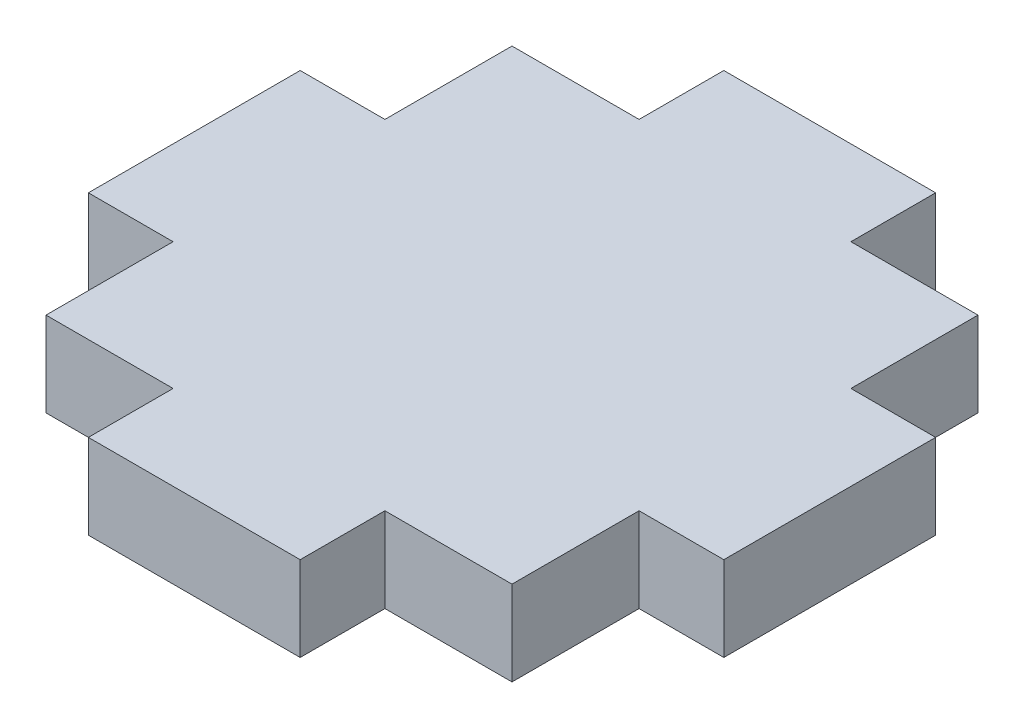
SolidWorks part; units mm, degrees
ref_plane "Front Plane" through (0, 0, 0) normal (0, 0, 1) x (1, 0, 0)
ref_plane "Top Plane" through (0, 0, 0) normal (0, 1, 0) x (1, 0, 0)
ref_plane "Right Plane" through (0, 0, 0) normal (1, 0, 0) x (0, 0, -1)
sketch "Sketch1" plane through (0, 0, 0) normal (0, 1, 0) x (1, 0, 0)
  line L1 (0, 0) -> (30, 0)
  line L2 (0, 0) -> (0, 30)
  line L3 (0, 30) -> (30, 30)
  line L4 (30, 0) -> (30, 30)
  line L9 (0, 30) -> (4, 30)
  line L10 (0, 30) -> (0, 0)
  line L11 (0, 0) -> (4, 0)
  line L12 (4, 30) -> (4, 0)
  line L13 (0, 0) -> (30, 0)
  line L14 (0, 0) -> (0, 4)
  line L15 (0, 4) -> (30, 4)
  line L16 (30, 0) -> (30, 4)
  line L17 (30, 0) -> (26, 0)
  line L18 (30, 0) -> (30, 30)
  line L19 (30, 30) -> (26, 30)
  line L20 (26, 0) -> (26, 30)
  line L21 (30, 30) -> (0, 30)
  line L22 (30, 30) -> (30, 26)
  line L23 (30, 26) -> (0, 26)
  line L24 (0, 30) -> (0, 26)
  line L25 (0, 20) -> (4, 20)
  line L26 (0, 20) -> (0, 10)
  line L27 (0, 10) -> (4, 10)
  line L28 (4, 20) -> (4, 10)
  line L29 (10, 26) -> (20, 26)
  line L30 (10, 26) -> (10, 30)
  line L31 (10, 30) -> (20, 30)
  line L32 (20, 26) -> (20, 30)
  line L33 (26, 20) -> (30, 20)
  line L34 (26, 20) -> (26, 10)
  line L35 (26, 10) -> (30, 10)
  line L36 (30, 20) -> (30, 10)
  line L37 (20, 4) -> (10, 4)
  line L38 (20, 4) -> (20, 0)
  line L39 (20, 0) -> (10, 0)
  line L40 (10, 4) -> (10, 0)
  point P29 (10, 2)
  dimension "D1" = 30
  dimension "D2" = 30
  dimension "D3" = 4
  dimension "D4" = 4
  dimension "D5" = 4
  dimension "D6" = 4
  dimension "D7" = 10
  dimension "D8" = 10
  dimension "D9" = 10
  dimension "D10" = 10
  dimension "D11" = 10
  dimension "D12" = 10
  dimension "D13" = 10
  dimension "D14" = 10
extrude "Boss-Extrude1" add sketch "Sketch1" along normal blind 4 contours L20 L23 L12 L15 | L15 L40 L13 L38 | L20 L35 L18 L33 | L23 L32 L21 L30 | L2 L27 L12 L25
